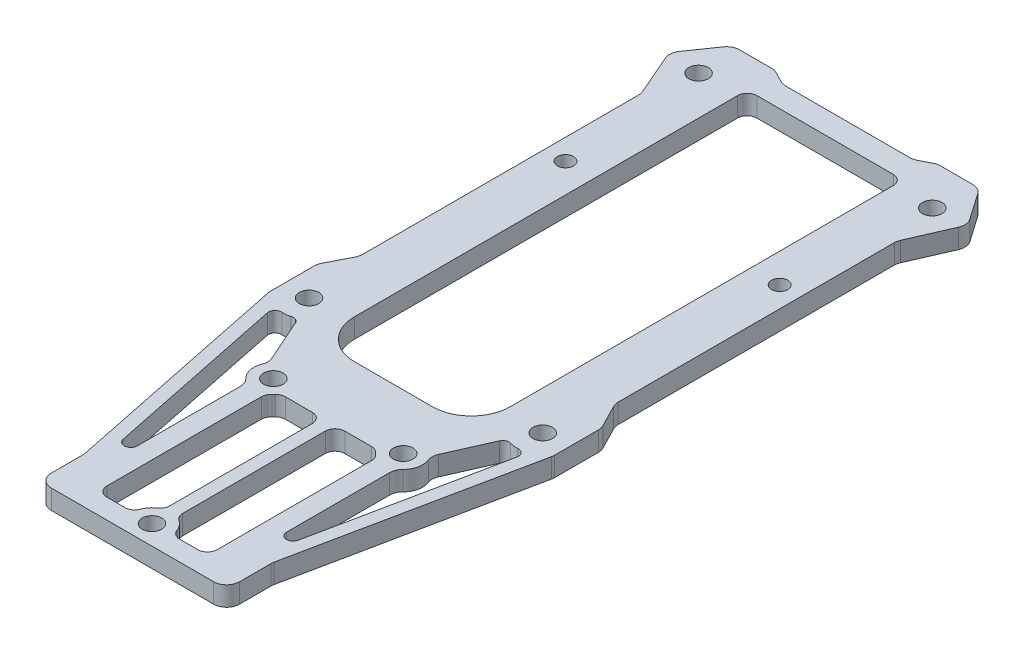
SolidWorks part; units mm, degrees
material "碳板"
ref_plane "前视基准面" through (0, 0, 0) normal (0, 0, 1) x (1, 0, 0)
ref_plane "上视基准面" through (0, 0, 0) normal (0, 1, 0) x (1, 0, 0)
ref_plane "右视基准面" through (0, 0, 0) normal (1, 0, 0) x (0, 0, -1)
sketch "草图1" plane through (0, 0, 0) normal (0, 1, 0) x (1, 0, 0)
  line L0 (0, 5.6483) -> (0, -5.1979) construction
  line L1 (10.0423, 35) -> (-10.0423, 35)
  line L2 (-18, 30) -> (18, 30) construction
  line L3 (-18, 30) -> (-18, -30) construction
  line L4 (-18, -30) -> (18, -30) construction
  line L5 (18, 30) -> (18, -30) construction
  line L6 (-18, 30) -> (18, -30) construction
  line L7 (-18, -30) -> (18, 30) construction
  line L8 (-10.0423, 35) -> (-12.5237, 36.2732)
  line L9 (-12.5237, 36.2732) -> (-19.0017, 36.2732)
  line L10 (-19.0017, 36.2732) -> (-23.0155, 30.5)
  line L11 (-23.0155, 30.5) -> (-19.6957, 22.8775)
  line L12 (-19.6957, 22.8775) -> (-19.6957, -20.553)
  line L13 (-19.6957, -20.553) -> (-21.8848, -24.8194)
  line L14 (-21.8848, -24.8194) -> (-21.8848, -32.2555)
  line L15 (-21.8848, -32.2555) -> (-14.5, -68.1231)
  line L16 (-14.5, -68.1231) -> (-14.5, -75.2)
  line L17 (-14.5, -75.2) -> (14.5, -75.2)
  line L18 (0, -20.0088) -> (0, -52.7088) construction
  line L19 (0, -72.2) -> (10, -43.5) construction
  line L20 (23.0155, 30.5) -> (19.6957, 22.8775)
  line L21 (19.0017, 36.2732) -> (23.0155, 30.5)
  line L22 (12.5237, 36.2732) -> (19.0017, 36.2732)
  line L23 (10.0423, 35) -> (12.5237, 36.2732)
  line L24 (19.6957, -20.553) -> (21.8848, -24.8194)
  line L25 (19.6957, 22.8775) -> (19.6957, -20.553)
  line L26 (21.8848, -24.8194) -> (21.8848, -32.2555)
  line L27 (21.8848, -32.2555) -> (14.5, -68.1231)
  line L28 (14.5, -68.1231) -> (14.5, -75.2)
  line L30 (-12, 31.5) -> (12, 31.5)
  line L31 (-12, 31.5) -> (-12, -35)
  line L32 (-12, -35) -> (12, -35)
  line L33 (12, 31.5) -> (12, -35)
  line L34 (-12, 31.5) -> (12, -35) construction
  line L35 (-12, -35) -> (12, 31.5) construction
  circle A0 centre (-18, 30) radius 1.5
  circle A1 centre (18, 30) radius 1.5
  circle A2 centre (18, -30) radius 1.5
  circle A3 centre (-18, -30) radius 1.5
  circle A4 centre (0, -72.2) radius 1.5
  circle A5 centre (-10, -43.5) radius 1.5
  circle A6 centre (10, -43.5) radius 1.5
  circle A7 centre (-16.5, 8) radius 1.25
  circle A8 centre (16.5, 8) radius 1.25
  point P1 (0, 0)
  point P34 (-21.8848, -28.5375)
  point P40 (0, 35)
  point P42 (21.8848, -28.5375)
  point P46 (0, -75.2)
  point P62 (0, -1.75)
  dimension "D1" = 3
  dimension "D4" = 3
  dimension "D7" = 73.5
  dimension "D14" = 2.5
  dimension "D15" = 33
  dimension "D16" = 22
  dimension "D2" = 60
  dimension "D3" = 36
  dimension "D5" = 28.7
  dimension "D6" = 20
  dimension "D8" = 3.5
  dimension "D9" = 5
  dimension "D10" = 66.5
  dimension "D11" = 24
  dimension "D12" = 29
  dimension "D13" = 3
extrude "凸台-拉伸1" add sketch "草图1" along normal blind 3
fillet "圆角1" radius 1.5 2 edges at (-12, 1.5, -31.5) (12, 1.5, -31.5)
sketch "草图2" plane through (0, 3, 0) normal (0, 1, 0) x (1, 0, 0)
  line L0 (0, 35) -> (0, -76.2089) construction
  line L1 (10.0423, 35) -> (-10.0423, 35) construction
  line L2 (-10, -43.5) -> (10, -43.5) construction
  line L3 (10, -68.8559) -> (10, -43.5) construction
  line L4 (-10, -43.5) -> (-18, -30) construction
  line L5 (-18, -30) -> (-10, -68.8559) construction
  line L6 (-10, -68.8559) -> (-10, -43.5) construction
  line L7 (-21.8848, -32.2555) -> (-14.5, -68.1231) construction
  line L8 (-21.6806, -23.3293) -> (-9.6296, -81.861)
  line L9 (-8.5, -80.9793) -> (-8.5, -43.0889)
  line L10 (-8.5, -43.0889) -> (-16.7096, -29.2353)
  line L11 (-11.5, -77.4529) -> (-11.5, -43.9111)
  line L12 (-11.5, -43.9111) -> (-23.3854, -17.0579)
  line L13 (-11.5, -68.8559) -> (-11.5, -43.9111) construction
  line L14 (-11.5, -43.9111) -> (-19.2904, -30.7647) construction
  line L15 (-8.5, -68.8559) -> (-8.5, -43.0889) construction
  line L16 (-10, -45) -> (10, -45)
  line L17 (-10, -42) -> (10, -42)
  line L18 (18, -30) -> (10, -68.8559) construction
  line L19 (10, -43.5) -> (18, -30) construction
  line L20 (11.5, -43.9111) -> (23.3854, -17.0579)
  line L21 (11.5, -77.4529) -> (11.5, -43.9111)
  line L22 (8.5, -43.0889) -> (16.7096, -29.2353)
  line L23 (8.5, -80.9793) -> (8.5, -43.0889)
  line L24 (-8.5, -72.1427) -> (8.5, -72.1427)
  line L25 (21.6806, -23.3293) -> (9.6296, -81.861)
  line L26 (-1, 35) -> (-1, -76.2089)
  line L27 (1, 35) -> (1, -76.2089)
  circle A11 centre (-18, -30) radius 4
  circle A12 centre (-10, -43.5) radius 3
  circle A13 centre (0, -72.2) radius 3
  circle A16 centre (10, -43.5) radius 3
  circle A17 centre (18, -30) radius 4
  dimension "D4" = 8
  dimension "D7" = 6
  dimension "D1" = 2
  dimension "D2" = 1.5
  dimension "D3" = 1.5
  dimension "D5" = 1.5
  dimension "D6" = 1.5
  dimension "D8" = 1
  dimension "D9" = 1
extrude "切除-拉伸1" cut sketch "草图2" against normal blind 3
fillet "圆角2" radius 1 6 edges at (11.5, 1.5, 72.7764) (-11.5, 1.5, 72.7764) (16.0994, 1.5, 33.5196) (-19.5478, 1.5, 33.6884) (19.5478, 1.5, 33.6884) (-16.0994, 1.5, 33.5196)
fillet "圆角3" radius 1.5 12 edges at (2.9995, 1.5, 72.1427) (-2.9995, 1.5, 72.1427) (-8.5, 1.5, 72.1427) (-8.5, 1.5, 46.0981) (-7.4019, 1.5, 45) (7.4019, 1.5, 45) (8.5, 1.5, 72.1427) (8.5, 1.5, 46.0981) (-1, 1.5, 69.3716) (-1, 1.5, 45) (1, 1.5, 69.3716) (1, 1.5, 45)
fillet "圆角4" radius 2 4 edges at (-11.5, 1.5, 46.0981) (11.5, 1.5, 46.0981) (12.4489, 1.5, 41.7671) (-12.4489, 1.5, 41.7671)
fillet "圆角5" radius 2 20 edges at (-12.5237, 1.5, -36.2732) (-10.0423, 1.5, -35) (10.0423, 1.5, -35) (12.5237, 1.5, -36.2732) (19.0017, 1.5, -36.2732) (23.0155, 1.5, -30.5) (19.6957, 1.5, -22.8775) (19.6957, 1.5, 20.553) (21.8848, 1.5, 24.8194) (21.8848, 1.5, 32.2555) (14.5, 1.5, 68.1231) (14.5, 1.5, 75.2) (-14.5, 1.5, 68.1231) (-21.8848, 1.5, 32.2555) (-21.8848, 1.5, 24.8194) (-19.6957, 1.5, 20.553) (-19.6957, 1.5, -22.8775) (-23.0155, 1.5, -30.5) (-19.0017, 1.5, -36.2732) (-14.5, 1.5, 75.2)
fillet "圆角6" radius 6 2 edges at (-12, 1.5, 35) (12, 1.5, 35)
